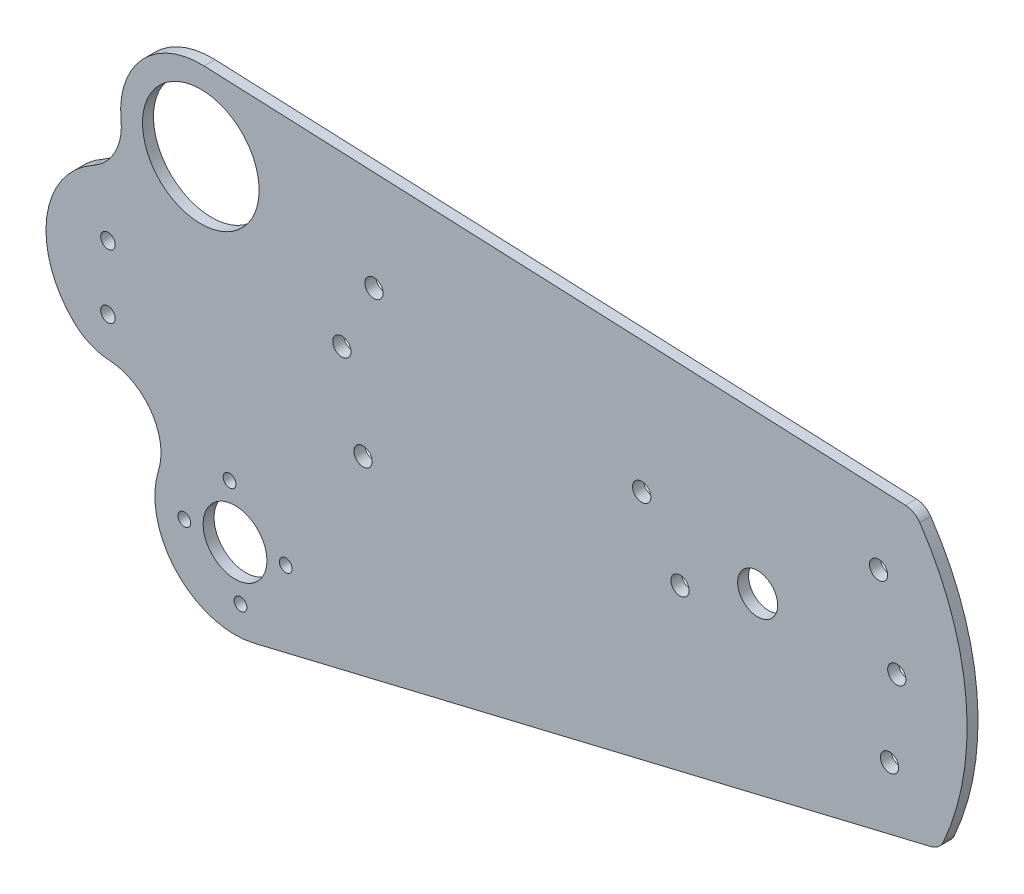
SolidWorks part; units mm, degrees
ref_plane "Front Plane" through (0, 0, 0) normal (0, 0, 1) x (1, 0, 0)
ref_plane "Top Plane" through (0, 0, 0) normal (0, 1, 0) x (1, 0, 0)
ref_plane "Right Plane" through (0, 0, 0) normal (1, 0, 0) x (0, 0, -1)
sketch "Sketch1" plane through (0, 0, 0) normal (0, 0, 1) x (1, 0, 0)
  line L0 (86.8854, -33.5) -> (-137.2004, -33.5) construction
  line L1 (-111.886, 49.4802) -> (80.595, 41.3179)
  line L2 (-115.2069, 49.6211) -> (-101.035, -81.6153) construction
  line L3 (-97.8208, -80.7688) -> (92.1699, -30.731) construction
  line L4 (78.7977, 41.3942) -> (86.7407, -32.1609) construction
  line L5 (-108.121, -15.9971) -> (82.7692, 4.6166) construction
  line L6 (91, -33.5) -> (-88.5, -33.5) construction
  line L7 (-97.4673, 5.5) -> (-155.3054, 5.5) construction
  line L8 (-138.3, -14) -> (-155.3054, -14) construction
  line L9 (-138.3, 5.5) -> (-138.3, -33.5) construction
  line L10 (-155.3054, 5.5) -> (-155.3054, -33.5) construction
  line L11 (40.0178, 33.5) -> (40.0178, -33.5) construction
  line L12 (-108.121, -83.2436) -> (87.5999, -36.3241)
  line L13 (-91.5, 33.5) -> (88, 33.5) construction
  line L14 (-68.3, -21.5) -> (-107.0746, -25.6872) construction
  circle A0 centre (40.0178, 0) radius 5.5
  circle A1 centre (-112.8181, 27.5) radius 14 construction
  circle A2 centre (-103.4238, -59.4942) radius 14 construction
  arc A3 (-91.5, 33.5) -> (-88.5, -33.5) centre (-18.0922, 3.2198) ccw construction
  circle A4 centre (-68.3, -21.5) radius 2.5
  circle A5 centre (-68.3, -21.5) radius 2.5 construction
  circle A6 centre (-138.3, -5.25) radius 2
  circle A7 centre (-138.3, -22.75) radius 2
  arc A8 (-142.3827, 10.6321) -> (-147.5429, -29.3643) centre (-130.3054, -11.2571) ccw
  arc A9 (-147.5429, -29.3643) -> (-137.2004, -33.5) centre (-137.2004, -18.5) ccw
  circle A10 centre (-112.8181, 27.5) radius 22
  arc A11 (87.5999, -36.3241) -> (91, -33.5) centre (86.4343, -31.4619) ccw
  circle A12 centre (-103.4238, -59.4942) radius 22
  arc A13 (91, -33.5) -> (84.5157, 39.1371) centre (22.6589, -2.9929) ccw
  arc A14 (91, -33.5) -> (88, 33.5) centre (22.6589, -2.9929) ccw construction
  arc A15 (84.5157, 39.1371) -> (80.595, 41.3179) centre (80.3831, 36.3224) ccw
  arc A17 (-124.4228, -52.9336) -> (-137.9704, -33.4802) centre (-138.7403, -48.4604) ccw
  arc A18 (-142.3827, 10.6321) -> (-134.7058, 25.2795) centre (-149.6292, 23.7656) ccw
  circle A19 centre (-74.1, 1.7) radius 2.5
  circle A20 centre (-65.3, 20) radius 2.5
  circle A21 centre (8.2, 8.3) radius 2.5
  circle A23 centre (18.7, -8.7) radius 2.5
  circle A25 centre (78.2, -0.1) radius 2.5
  circle A26 centre (76.2, -22) radius 2.5
  circle A27 centre (73.2, 22.3) radius 2.5
  circle A28 centre (73.2, 22.3) radius 2.5 construction
  circle A29 centre (78.2, -0.1) radius 2.5 construction
  circle A31 centre (8.2, 8.3) radius 2.5 construction
  circle A32 centre (18.7, -8.7) radius 2.5 construction
  circle A33 centre (76.2, -22) radius 2.5 construction
  circle A34 centre (-74.1, 1.7) radius 2.5 construction
  circle A35 centre (-65.3, 20) radius 2.5 construction
  circle A36 centre (-114.3212, 41.4191) radius 1.75
  circle A37 centre (-98.899, 29.0031) radius 1.75
  circle A38 centre (-111.315, 13.5809) radius 1.75
  circle A39 centre (-126.7372, 25.9969) radius 1.75
  circle A40 centre (-104.9269, -45.5752) radius 1.75
  circle A41 centre (-89.5048, -57.9912) radius 1.75
  circle A42 centre (-101.9208, -73.4133) radius 1.75
  circle A43 centre (-117.3429, -60.9973) radius 1.75
  circle A44 centre (40.0178, 0) radius 35 construction
  circle A45 centre (40.0178, 0) radius 43
  circle A49 centre (-103.4238, -59.4942) radius 16
  circle A50 centre (-112.8181, 27.5) radius 16
  circle A51 centre (-112.8181, 27.5) radius 8.75
  circle A52 centre (-103.4238, -59.4942) radius 8.75
  arc A53 (91, -33.5) -> (88, 33.5) centre (22.6589, -2.9929) ccw construction
  point P52 (82.7692, 4.6166)
  point P109 (-112.8181, 27.5)
  point P118 (-103.4238, -59.4942)
  dimension "D5" = 4
  dimension "D6" = 25
  dimension "D9" = 15
  dimension "D13" = 10
  dimension "D14" = 28
  dimension "D11" = 44
  dimension "D15" = 3.5
  dimension "D12" = 70
  dimension "D19" = 11
  dimension "D20" = 17.5
  dimension "D22" = 32
  dimension "D2" = 39
  dimension "D3" = 70
  dimension "D4" = 17.5
  dimension "D7" = 14
  dimension "D8" = 10
  dimension "D10" = 87.5
  dimension "D21" = 192
  dimension "D23" = 39
  dimension "D18" = 8
  dimension "D16" = 4
  dimension "D17" = 4
extrude "Boss-Extrude1" add sketch "Sketch1" along normal blind 3
